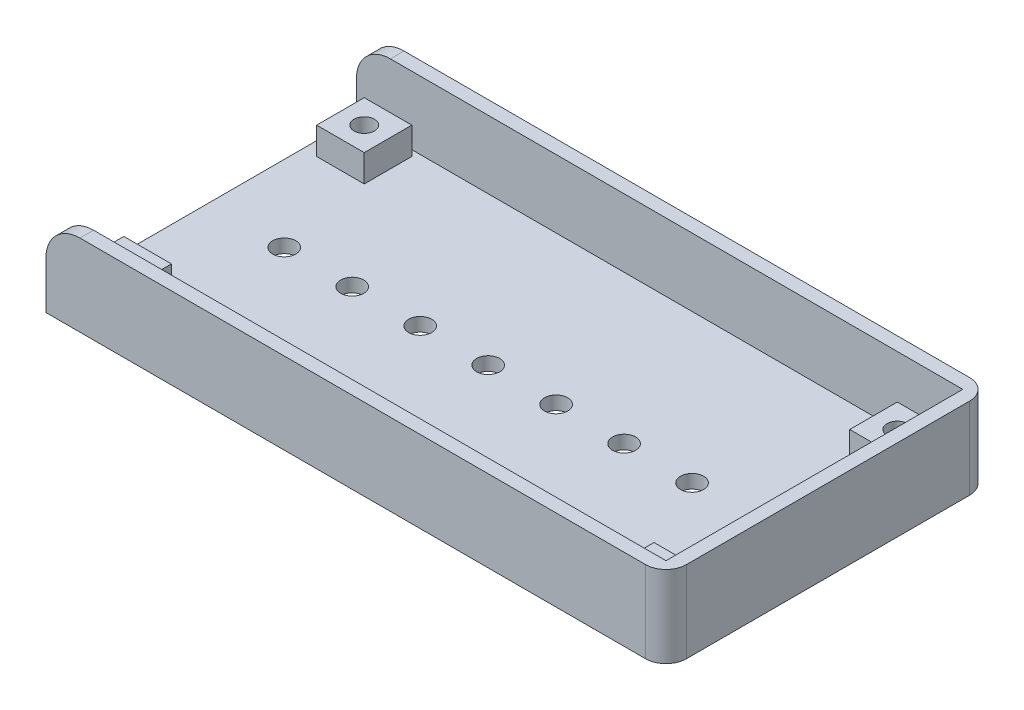
SolidWorks part; units mm, degrees
ref_plane "Front Plane" through (0, 0, 0) normal (0, 0, 1) x (1, 0, 0)
ref_plane "Top Plane" through (0, 0, 0) normal (0, 1, 0) x (1, 0, 0)
ref_plane "Right Plane" through (0, 0, 0) normal (1, 0, 0) x (0, 0, -1)
sketch "Sketch1" plane through (0, 0, 0) normal (0, 1, 0) x (1, 0, 0)
  line L0 (-2, -2) -> (-2, 45.67)
  line L1 (0, 0) -> (87.22, 0) construction
  line L2 (0, 0) -> (0, 43.67) construction
  line L3 (0, 43.67) -> (87.22, 43.67) construction
  line L4 (87.22, 0) -> (87.22, 43.67) construction
  line L5 (-2, 45.67) -> (89.22, 45.67)
  line L6 (89.22, -2) -> (89.22, 45.67)
  line L7 (-2, -2) -> (89.22, -2)
  line L8 (-2, 21.835) -> (89.22, 21.835) construction
  circle A1 centre (79.22, 21.835) radius 1.7
  circle A2 centre (69.22, 21.835) radius 1.7
  circle A3 centre (59.22, 21.835) radius 1.7
  circle A4 centre (49.22, 21.835) radius 1.7
  circle A5 centre (39.22, 21.835) radius 1.7
  circle A6 centre (29.22, 21.835) radius 1.7
  circle A7 centre (19.22, 21.835) radius 1.7
  circle A8 centre (9.22, 21.835) radius 1.7
  dimension "D4" = 10
  dimension "D5" = 3.4
  dimension "D1" = 87.22
  dimension "D2" = 43.67
  dimension "D3" = 2
  dimension "D6" = 8
extrude "Boss-Extrude1" add sketch "Sketch1" along normal blind 2 contours A8 L8 L0 L7 L6 A1 A2 A3 A4 A5 A6 A7 | A8 L8 A7 A6 A5 A4 A3 A2 A1 L6 L5 L0
sketch "Sketch2" plane through (0, 2, 0) normal (0, 1, 0) x (1, 0, 0)
  line L0 (-2, 0) -> (-2, -2)
  line L9 (0, 43.67) -> (0, 0)
  line L10 (0, 0) -> (87.22, 0)
  line L11 (87.22, 0) -> (87.22, 43.67)
  line L12 (87.22, 43.67) -> (0, 43.67)
  line L14 (0, 0) -> (87.22, 0)
  line L15 (87.22, 0) -> (87.22, 43.67)
  line L16 (87.22, 43.67) -> (0, 43.67)
  line L17 (0, 43.67) -> (-2, 43.67)
  line L18 (0, 0) -> (-2, 0)
  line L21 (-2, 45.67) -> (-2, -2)
  line L22 (-2, -2) -> (89.22, -2)
  line L23 (89.22, -2) -> (89.22, 45.67)
  line L24 (89.22, 45.67) -> (-2, 45.67)
  line L25 (-2, 45.67) -> (-2, 43.67)
  line L26 (-2, -2) -> (89.22, -2)
  line L27 (89.22, -2) -> (89.22, 45.67)
  line L28 (89.22, 45.67) -> (-2, 45.67)
  dimension "D1" = 2
  dimension "D2" = 0
extrude "Boss-Extrude2" add sketch "Sketch2" along normal blind 10
sketch "Sketch3" plane through (0, 2, 0) normal (0, 1, 0) x (1, 0, 0)
  line L0 (-2, 43.67) -> (87.22, 43.67) construction
  line L7 (87.22, 43.67) -> (87.22, 0) construction
  line B0 (85.0188, 43.235) -> (78.0188, 43.235)
  line B1 (85.0188, 43.235) -> (85.0188, 36.235)
  line B2 (85.0188, 36.235) -> (78.0188, 36.235)
  line B3 (78.0188, 43.235) -> (78.0188, 36.235)
  circle B4 centre (81.5188, 39.735) radius 1.5
  line B5 (85.0188, 0.435) -> (78.0188, 0.435)
  line B6 (85.0188, 0.435) -> (85.0188, 7.435)
  line B7 (85.0188, 7.435) -> (78.0188, 7.435)
  line B8 (78.0188, 0.435) -> (78.0188, 7.435)
  circle B9 centre (81.5188, 3.935) radius 1.5
  line B10 (0.02, 42.8) -> (7.02, 42.8)
  line B11 (0.02, 42.8) -> (0.02, 35.8)
  line B12 (0.02, 35.8) -> (7.02, 35.8)
  line B13 (7.02, 42.8) -> (7.02, 35.8)
  circle B14 centre (3.52, 39.3) radius 1.5
  line B15 (0.0188, 0.435) -> (7.0188, 0.435)
  line B16 (0.0188, 0.435) -> (0.0188, 7.435)
  line B17 (0.0188, 7.435) -> (7.0188, 7.435)
  line B18 (7.0188, 0.435) -> (7.0188, 7.435)
  circle B19 centre (3.5188, 3.935) radius 1.5
  dimension "D3" = 35.8
  dimension "D1" = 78
  dimension "D2" = 78
  dimension "D4" = 83.7
  dimension "D5" = 0.435
sketch_block_instance "Block1-1"
sketch_block "Block1" parameters "D3"=3, "D1"=7, "D2"=7
sketch_block_instance "Block1-2"
sketch_block_instance "Block1-3"
sketch_block_instance "Block1-4"
extrude "Boss-Extrude3" add sketch "Sketch3" along normal blind 4
fillet "Fillet1" radius 5 2 edges at (-2, 12, 1) (-2, 12, -44.67)
fillet "Fillet2" radius 3 2 edges at (89.22, 6, -45.67) (89.22, 6, 2)
